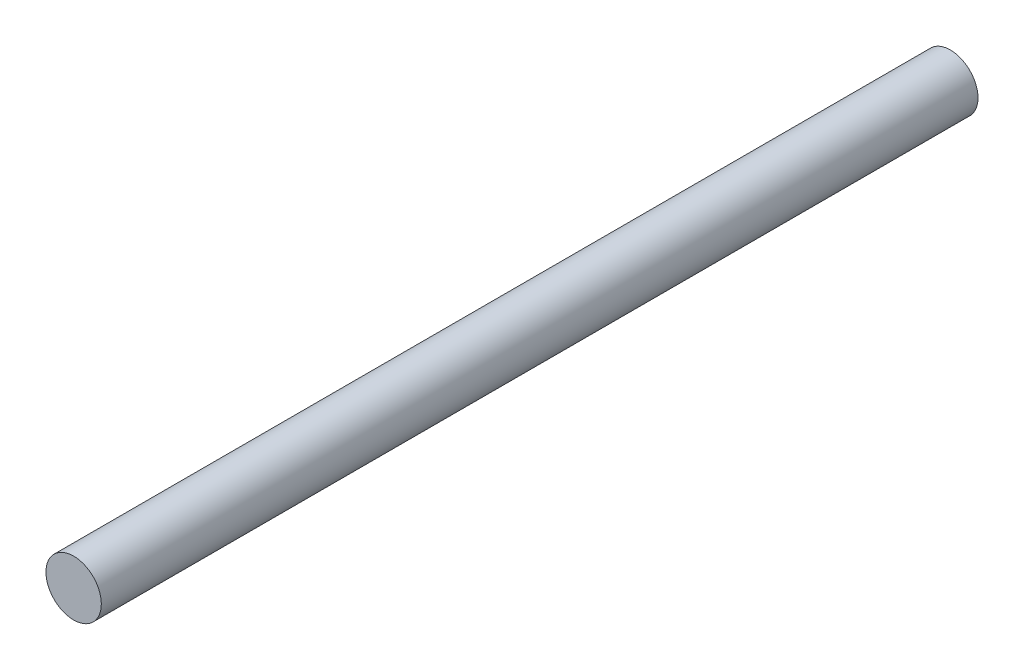
SolidWorks part; units mm, degrees
ref_plane "Plano frontal" through (0, 0, 0) normal (0, 0, 1) x (1, 0, 0)
ref_plane "Plano superior" through (0, 0, 0) normal (0, 1, 0) x (1, 0, 0)
ref_plane "Plano direito" through (0, 0, 0) normal (1, 0, 0) x (0, 0, -1)
sketch "Esboço1" plane through (0, 0, 0) normal (0, 0, 1) x (1, 0, 0)
  circle A0 centre (0, 0) radius 3
  dimension "D1" = 6
extrude "Ressalto-extrusão1" add sketch "Esboço1" along normal blind 95
